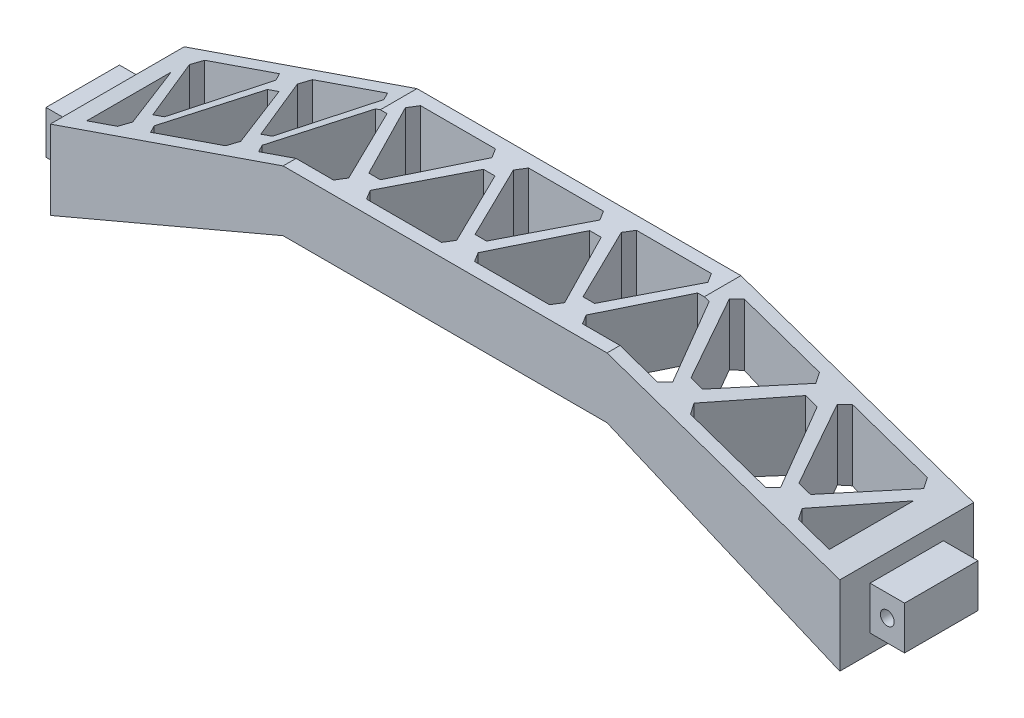
SolidWorks part; units mm, degrees
ref_plane "Alzado" through (0, 0, 0) normal (0, 0, 1) x (1, 0, 0)
ref_plane "Planta" through (0, 0, 0) normal (0, 1, 0) x (1, 0, 0)
ref_plane "Vista lateral" through (0, 0, 0) normal (1, 0, 0) x (0, 0, -1)
sketch "Croquis1" plane through (0, 0, 0) normal (0, 0, 1) x (1, 0, 0)
  line L0 (-37.5, 7) -> (-91.3946, -11.5574)
  line L1 (-37.5, 7) -> (37.5, 7)
  line L2 (-37.5, 7) -> (-37.5, -7)
  line L3 (-37.5, -7) -> (37.5, -7)
  line L4 (37.5, 7) -> (37.5, -7)
  line L5 (-37.5, 7) -> (37.5, -7) construction
  line L6 (-37.5, -7) -> (37.5, 7) construction
  line L7 (-91.3946, -11.5574) -> (-91.3946, -29.8774)
  line L8 (-91.3946, -29.8774) -> (-37.5, -7)
  line L9 (0, 7) -> (0, -7)
  line L10 (91.3946, -29.8774) -> (37.5, -7)
  line L11 (91.3946, -11.5574) -> (91.3946, -29.8774)
  line L12 (37.5, 7) -> (91.3946, -11.5574)
  point P0 (0, 0)
  dimension "D1" = 75
  dimension "D2" = 14
  dimension "D3" = 57
  dimension "D4" = 161
  dimension "D5" = 18.32
extrude "Saliente-Extruir1" add sketch "Croquis1" along normal mid plane 31 contours L7 L8 L2 L0 | L12 L4 L10 L11 | L1 L9 L3 L4 | L9 L1 L2 L3
sketch "Croquis2" plane through (-91.3946, 0, 0) normal (-1, 0, 0) x (0, 0, 1)
  line L1 (15.5, -29.8774) -> (-15.5, -29.8774) construction
  line L2 (-8.5, -25.7174) -> (8.5, -25.7174)
  line L3 (-8.5, -25.7174) -> (-8.5, -15.7174)
  line L4 (-8.5, -15.7174) -> (8.5, -15.7174)
  line L5 (8.5, -25.7174) -> (8.5, -15.7174)
  line L6 (-8.5, -25.7174) -> (8.5, -15.7174) construction
  line L7 (-8.5, -15.7174) -> (8.5, -25.7174) construction
  line L8 (15.5, -11.5574) -> (15.5, -29.8774) construction
  point P4 (0, -20.7174)
  dimension "D1" = 4.16
  dimension "D2" = 7
  dimension "D3" = 17
  dimension "D4" = 10
extrude "Saliente-Extruir2" add sketch "Croquis2" along normal blind 8
sketch "Croquis3" plane through (0, 0, 8.5) normal (0, 0, 1) x (1, 0, 0)
  line L0 (-99.3946, -15.7174) -> (-91.3946, -25.7174) construction
  line L6 (-97.37, -18.2481) -> (-93.4191, -23.1867) construction
  circle A0 centre (-95.3946, -20.7174) radius 1.6
  point P4 (-95.3946, -20.7174)
  dimension "D1" = 3.2
extrude "Cortar-Extruir1" cut sketch "Croquis3" against normal through all
mirror "Simetría1" about plane through (0, 0, 0) normal (1, 0, 0) of "Cortar-Extruir1", "Saliente-Extruir2"
sketch "Croquis4" plane through (0, 7, 0) normal (0, 1, 0) x (1, 0, 0)
  line L0 (-8.675, 12.5) -> (8.675, 12.5)
  line L3 (-37.5, 15.5) -> (37.5, 15.5) construction
  line L6 (-8.675, 12.5) -> (-10.0153, 10.3307)
  line L7 (-37.5, -15.5) -> (37.5, -15.5) construction
  line L9 (8.675, 12.5) -> (10.0153, 10.3307)
  line L11 (-1.5444, -7.02) -> (1.1356, -7.02)
  line L12 (-1.5444, -7.02) -> (-10.0153, 10.3307)
  line L13 (10.0153, 10.3307) -> (1.1356, -7.02)
  line L14 (3.8246, -12.5) -> (2.4843, -10.3307)
  line L15 (21.1746, -12.5) -> (22.5149, -10.3307)
  line L16 (10.9552, 7.02) -> (13.6352, 7.02)
  line L17 (10.9552, 7.02) -> (2.4843, -10.3307)
  line L18 (22.5149, -10.3307) -> (13.6352, 7.02)
  line L19 (3.8246, -12.5) -> (21.1746, -12.5)
  line L21 (0, 0) -> (0, 15.5) construction
  line L22 (35.0153, 10.3307) -> (26.1356, -7.02)
  line L23 (23.4556, -7.02) -> (26.1356, -7.02)
  line L24 (23.4556, -7.02) -> (14.9847, 10.3307)
  line L25 (16.325, 12.5) -> (14.9847, 10.3307)
  line L26 (16.325, 12.5) -> (33.675, 12.5)
  line L27 (33.675, 12.5) -> (35.0153, 10.3307)
  line L28 (28.8246, -12.5) -> (27.4843, -10.3307)
  line L29 (35.9552, 7.02) -> (27.4843, -10.3307)
  line L30 (35.9552, 7.02) -> (38.6352, 7.02)
  line L31 (47.5149, -10.3307) -> (38.6352, 7.02)
  line L32 (46.1746, -12.5) -> (47.5149, -10.3307)
  line L33 (28.8246, -12.5) -> (46.1746, -12.5)
  line L34 (60.0153, 10.3307) -> (51.1356, -7.02)
  line L35 (48.4556, -7.02) -> (51.1356, -7.02)
  line L36 (48.4556, -7.02) -> (39.9847, 10.3307)
  line L37 (41.325, 12.5) -> (39.9847, 10.3307)
  line L38 (41.325, 12.5) -> (58.675, 12.5)
  line L39 (58.675, 12.5) -> (60.0153, 10.3307)
  line L40 (53.8246, -12.5) -> (52.4843, -10.3307)
  line L41 (60.9552, 7.02) -> (52.4843, -10.3307)
  line L42 (60.9552, 7.02) -> (63.6352, 7.02)
  line L43 (72.5149, -10.3307) -> (63.6352, 7.02)
  line L44 (71.1746, -12.5) -> (72.5149, -10.3307)
  line L45 (53.8246, -12.5) -> (71.1746, -12.5)
  line L46 (85.0153, 10.3307) -> (76.1356, -7.02)
  line L47 (73.4556, -7.02) -> (76.1356, -7.02)
  line L48 (73.4556, -7.02) -> (64.9847, 10.3307)
  line L49 (66.325, 12.5) -> (64.9847, 10.3307)
  line L50 (66.325, 12.5) -> (83.675, 12.5)
  line L51 (83.675, 12.5) -> (85.0153, 10.3307)
  line L52 (78.8246, -12.5) -> (77.4843, -10.3307)
  line L53 (85.9552, 7.02) -> (77.4843, -10.3307)
  line L57 (78.8246, -12.5) -> (85.9552, -12.5)
  line L58 (85.9552, 7.02) -> (85.9552, -12.5)
  line L59 (-3.8246, -12.5) -> (-2.4843, -10.3307)
  line L60 (85.9552, 7.02) -> (88.6352, 7.02) [skipped]
  line L61 (97.5149, -10.3307) -> (88.6352, 7.02) [skipped]
  line L62 (96.1746, -12.5) -> (97.5149, -10.3307) [skipped]
  line L63 (-83.675, 12.5) -> (-85.0153, 10.3307)
  line L64 (-66.325, 12.5) -> (-83.675, 12.5)
  line L65 (-66.325, 12.5) -> (-64.9847, 10.3307)
  line L66 (-60.9552, 7.02) -> (-63.6352, 7.02)
  line L67 (-58.675, 12.5) -> (-60.0153, 10.3307)
  line L68 (-41.325, 12.5) -> (-58.675, 12.5)
  line L69 (-41.325, 12.5) -> (-39.9847, 10.3307)
  line L70 (-35.9552, 7.02) -> (-38.6352, 7.02)
  line L71 (-33.675, 12.5) -> (-35.0153, 10.3307)
  line L72 (-16.325, 12.5) -> (-33.675, 12.5)
  line L73 (-16.325, 12.5) -> (-14.9847, 10.3307)
  line L74 (-10.9552, 7.02) -> (-13.6352, 7.02)
  line L75 (-85.9552, 7.02) -> (-85.9552, -12.5)
  line L76 (-78.8246, -12.5) -> (-85.9552, -12.5)
  line L77 (-85.9552, 7.02) -> (-77.4843, -10.3307)
  line L78 (-78.8246, -12.5) -> (-77.4843, -10.3307)
  line L79 (-73.4556, -7.02) -> (-64.9847, 10.3307)
  line L80 (-73.4556, -7.02) -> (-76.1356, -7.02)
  line L81 (-85.0153, 10.3307) -> (-76.1356, -7.02)
  line L82 (-53.8246, -12.5) -> (-71.1746, -12.5)
  line L83 (-71.1746, -12.5) -> (-72.5149, -10.3307)
  line L84 (-72.5149, -10.3307) -> (-63.6352, 7.02)
  line L85 (-60.9552, 7.02) -> (-52.4843, -10.3307)
  line L86 (-53.8246, -12.5) -> (-52.4843, -10.3307)
  line L87 (-48.4556, -7.02) -> (-39.9847, 10.3307)
  line L88 (-48.4556, -7.02) -> (-51.1356, -7.02)
  line L89 (-60.0153, 10.3307) -> (-51.1356, -7.02)
  line L90 (-28.8246, -12.5) -> (-46.1746, -12.5)
  line L91 (-46.1746, -12.5) -> (-47.5149, -10.3307)
  line L92 (-47.5149, -10.3307) -> (-38.6352, 7.02)
  line L93 (-35.9552, 7.02) -> (-27.4843, -10.3307)
  line L94 (-28.8246, -12.5) -> (-27.4843, -10.3307)
  line L95 (-23.4556, -7.02) -> (-14.9847, 10.3307)
  line L96 (-23.4556, -7.02) -> (-26.1356, -7.02)
  line L97 (-35.0153, 10.3307) -> (-26.1356, -7.02)
  line L98 (-3.8246, -12.5) -> (-21.1746, -12.5)
  line L99 (-22.5149, -10.3307) -> (-13.6352, 7.02)
  line L100 (-10.9552, 7.02) -> (-2.4843, -10.3307)
  line L101 (-21.1746, -12.5) -> (-22.5149, -10.3307)
  point P16 (0, 12.5)
  dimension "D1" = 3
  dimension "D2" = 17.35
  dimension "D3" = 121.71
  dimension "D4" = 2.55
  dimension "D5" = 3
  dimension "D6" = 2.68
  dimension "D7" = 3.8246
  dimension "D8" = 17.35
  dimension "D9" = 4
extrude "Cortar-Extruir2" cut sketch "Croquis4" against normal through all
